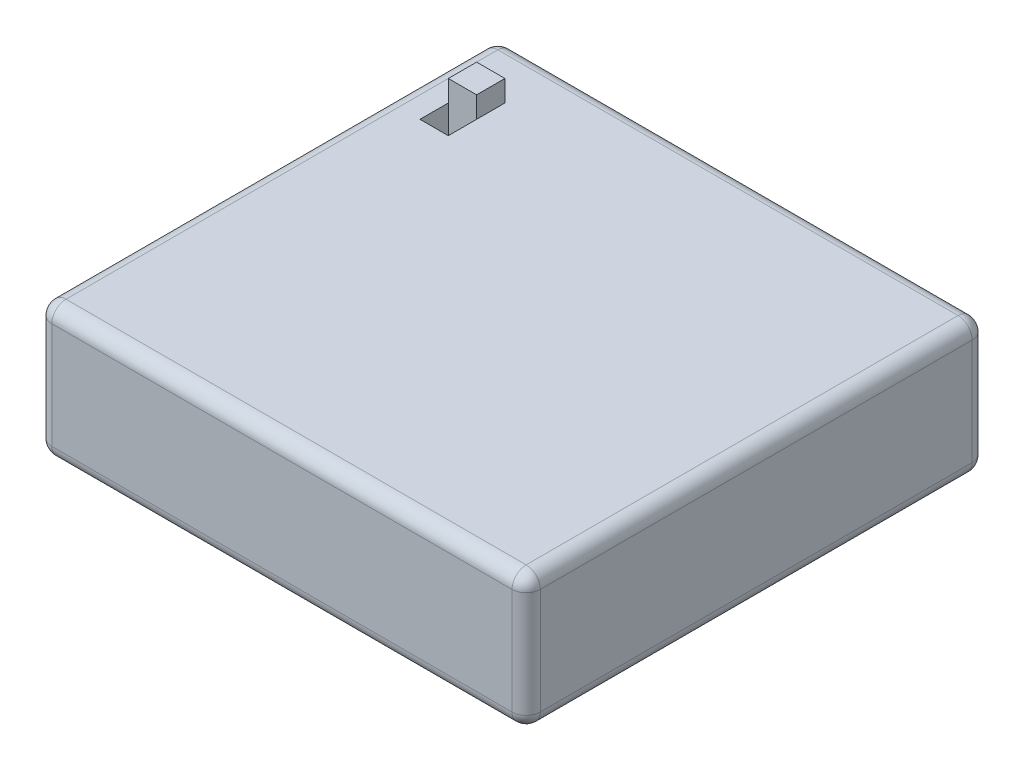
SolidWorks part; units mm, degrees
ref_plane "Front" through (0, 0, 0) normal (0, 0, 1) x (1, 0, 0)
ref_plane "Top" through (0, 0, 0) normal (0, 1, 0) x (1, 0, 0)
ref_plane "Right" through (0, 0, 0) normal (1, 0, 0) x (0, 0, -1)
sketch "Эскиз1" plane through (0, 0, 0) normal (0, 0, 1) x (1, 0, 0)
  line L1 (32.5, -9.5) -> (-32.5, -9.5)
  line L2 (34.5, -7.5) -> (34.5, 7.5)
  line L3 (32.5, 9.5) -> (-32.5, 9.5)
  line L4 (-34.5, -7.5) -> (-34.5, 7.5)
  line L5 (34.5, -9.5) -> (-34.5, 9.5) construction
  line L6 (34.5, 9.5) -> (-34.5, -9.5) construction
  arc A0 (-32.5, 9.5) -> (-34.5, 7.5) centre (-32.5, 7.5) ccw
  arc A1 (-32.5, -9.5) -> (-34.5, -7.5) centre (-32.5, -7.5) cw
  arc A2 (32.5, -9.5) -> (34.5, -7.5) centre (32.5, -7.5) ccw
  arc A3 (34.5, 7.5) -> (32.5, 9.5) centre (32.5, 7.5) ccw
  point P0 (0, 0)
  dimension "D3" = 2
  dimension "D4" = 2
  dimension "D1" = 19
  dimension "D2" = 69
extrude "Бобышка-Вытянуть1" add sketch "Эскиз1" along normal blind 65
fillet "Скругление1" radius 2 16 edges at (33.9142, 8.9142, 65) (34.5, 0, 65) (33.9142, -8.9142, 65) (0, -9.5, 65) (-33.9142, -8.9142, 65) (-34.5, 0, 65) (-33.9142, 8.9142, 65) (-34.5, 0, 0) (-33.9142, -8.9142, 0) (0, -9.5, 0) (33.9142, -8.9142, 0) (34.5, 0, 0) (33.9142, 8.9142, 0) (-33.9142, 8.9142, 0) (0, 9.5, 65) (0, 9.5, 0)
sketch "Эскиз2" plane through (0, 9.5, 0) normal (0, 1, 0) x (1, 0, 0)
  line L0 (0, -63) -> (0, -2) construction
  line L1 (-32.5, -63) -> (32.5, -63) construction
  line L2 (32.5, -2) -> (-32.5, -2) construction
  line L3 (0, -12) -> (-27.5, -12) construction
  line L4 (-32.5, -12) -> (-29.5, -12) construction
  line L5 (-25.5, -16) -> (-29.5, -16)
  line L6 (-25.5, -16) -> (-25.5, -8)
  line L7 (-25.5, -8) -> (-29.5, -8)
  line L8 (-29.5, -16) -> (-29.5, -8)
  line L9 (-25.5, -16) -> (-29.5, -8) construction
  line L10 (-25.5, -8) -> (-29.5, -16) construction
  line L12 (-32.5, -63) -> (-32.5, -2) construction
  line L13 (-29.5, -12) -> (-27.5, -12) construction
  dimension "D1" = 8
  dimension "D2" = 4
  dimension "D3" = 10
  dimension "D4" = 3
extrude "Вырез-Вытянуть1" cut sketch "Эскиз2" against normal blind 4
sketch "Эскиз4" plane through (0, 5.5, 0) normal (0, 1, 0) x (1, 0, 0)
  line L0 (-27.5, -8) -> (-27.5, -10) construction
  line L1 (-25.5, -8) -> (-29.5, -8) construction
  line L2 (-27.5, -10) -> (-27.5, -16) construction
  line L3 (-29.5, -16) -> (-25.5, -16) construction
  line L7 (-25.5, -12) -> (-29.5, -12)
  line L8 (-25.5, -12) -> (-25.5, -8)
  line L9 (-25.5, -8) -> (-29.5, -8)
  line L10 (-29.5, -12) -> (-29.5, -8)
  line L11 (-25.5, -12) -> (-29.5, -8) construction
  line L12 (-25.5, -8) -> (-29.5, -12) construction
  dimension "D1" = 4
  dimension "D2" = 4
  dimension "D3" = 2
extrude "Бобышка-Вытянуть2" add sketch "Эскиз4" along normal blind 7
sketch "Эскиз5" plane through (-34.5, 0, 0) normal (-1, 0, 0) x (0, 0, 1)
  line L0 (63, 0) -> (57, 0) construction
  line L1 (63, -7.5) -> (63, 7.5) construction
  line L2 (57, 0) -> (55, 0) construction
  line L4 (55, 0) -> (2, 0) construction
  line L5 (2, 7.5) -> (2, -7.5) construction
  circle A0 centre (55, 0) radius 0.5
  circle A1 centre (57, 0) radius 0.5
  dimension "D2" = 1
  dimension "D3" = 1
  dimension "D1" = 6
  dimension "D4" = 2
extrude "Бобышка-Вытянуть3" add sketch "Эскиз5" along normal blind 5
